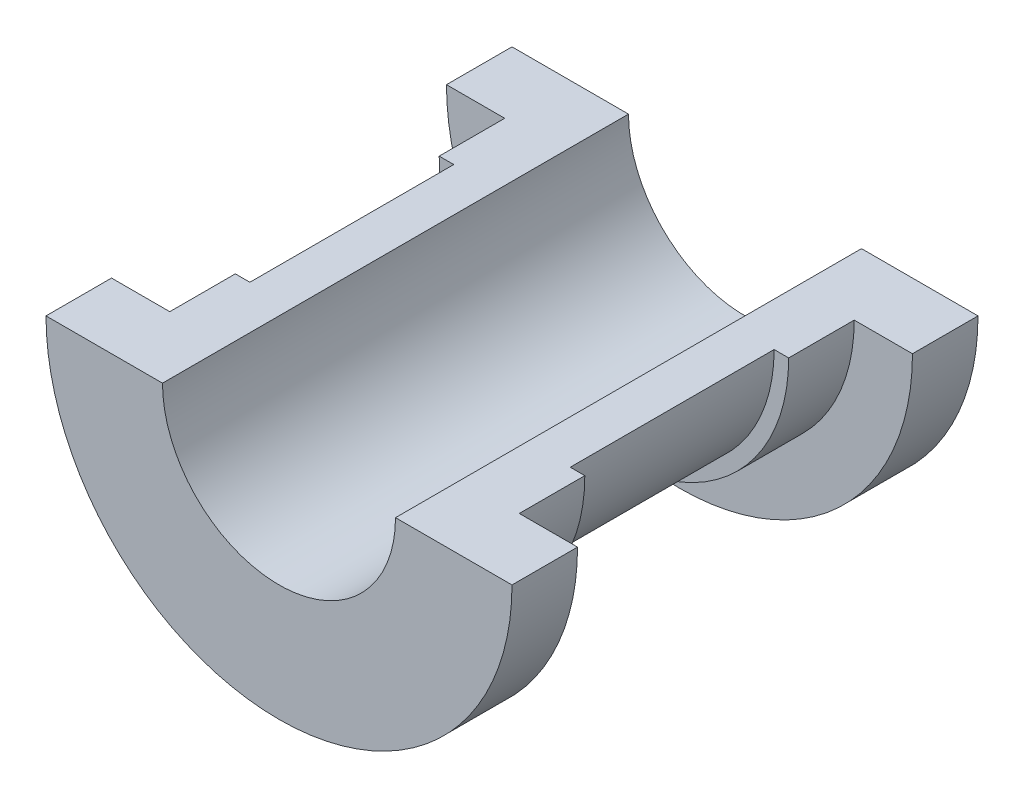
SolidWorks part; units mm, degrees
ref_plane "Front Plane" through (0, 0, 0) normal (0, 0, 1) x (1, 0, 0)
ref_plane "Top Plane" through (0, 0, 0) normal (0, 1, 0) x (1, 0, 0)
ref_plane "Right Plane" through (0, 0, 0) normal (1, 0, 0) x (0, 0, -1)
sketch "Sketch1" plane through (0, 0, 0) normal (0, 0, 1) x (1, 0, 0)
  circle A0 centre (0, 0) radius 16
  circle A2 centre (0, 0) radius 22
  dimension "D1" = 32
  dimension "D2" = 44
extrude "Boss-Extrude2" add sketch "Sketch1" along normal mid plane 14
sketch "Sketch3" plane through (0, 0, 7) normal (0, 0, 1) x (1, 0, 0)
  circle A3 centre (0, 0) radius 24
  dimension "D1" = 48
extrude "Boss-Extrude6" add sketch "Sketch3" along normal blind 9
sketch "Sketch6" plane through (0, 0, 16) normal (0, 0, 1) x (1, 0, 0)
  circle A0 centre (0, 0) radius 32
  dimension "64" = 64
extrude "Boss-Extrude7" add sketch "Sketch6" along normal blind 9
sketch "Sketch7" plane through (0, 0, -7) normal (0, 0, -1) x (-1, 0, 0)
  circle A0 centre (0, 0) radius 16 construction
  circle A3 centre (0, 0) radius 16
extrude "Cut-Extrude2" cut sketch "Sketch7" against normal through all
mirror "Mirror3" about plane through (0, 0, -7) normal (0, 0, 1) of bodies 120
sketch "Sketch8" plane through (0, 0, 25) normal (0, 0, 1) x (1, 0, 0)
  line L0 (-35.3721, 0) -> (34.5702, 0)
extrude "Cut-Extrude3" cut sketch "Sketch8" against normal through all
